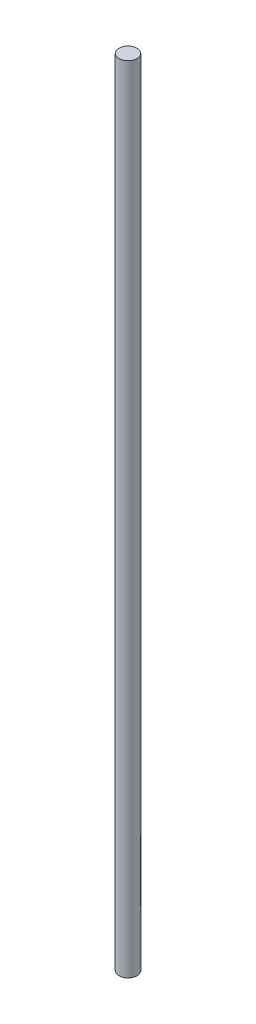
SolidWorks part; units mm, degrees
ref_plane "Front Plane" through (0, 0, 0) normal (0, 0, 1) x (1, 0, 0)
ref_plane "Top Plane" through (0, 0, 0) normal (0, 1, 0) x (1, 0, 0)
ref_plane "Right Plane" through (0, 0, 0) normal (1, 0, 0) x (0, 0, -1)
sketch "Sketch1" plane through (0, 0, 0) normal (0, 1, 0) x (1, 0, 0)
  circle A0 centre (0, 0) radius 3.175
  dimension "D1" = 6.35
extrude "Boss-Extrude1" add sketch "Sketch1" along normal mid plane 279.4
